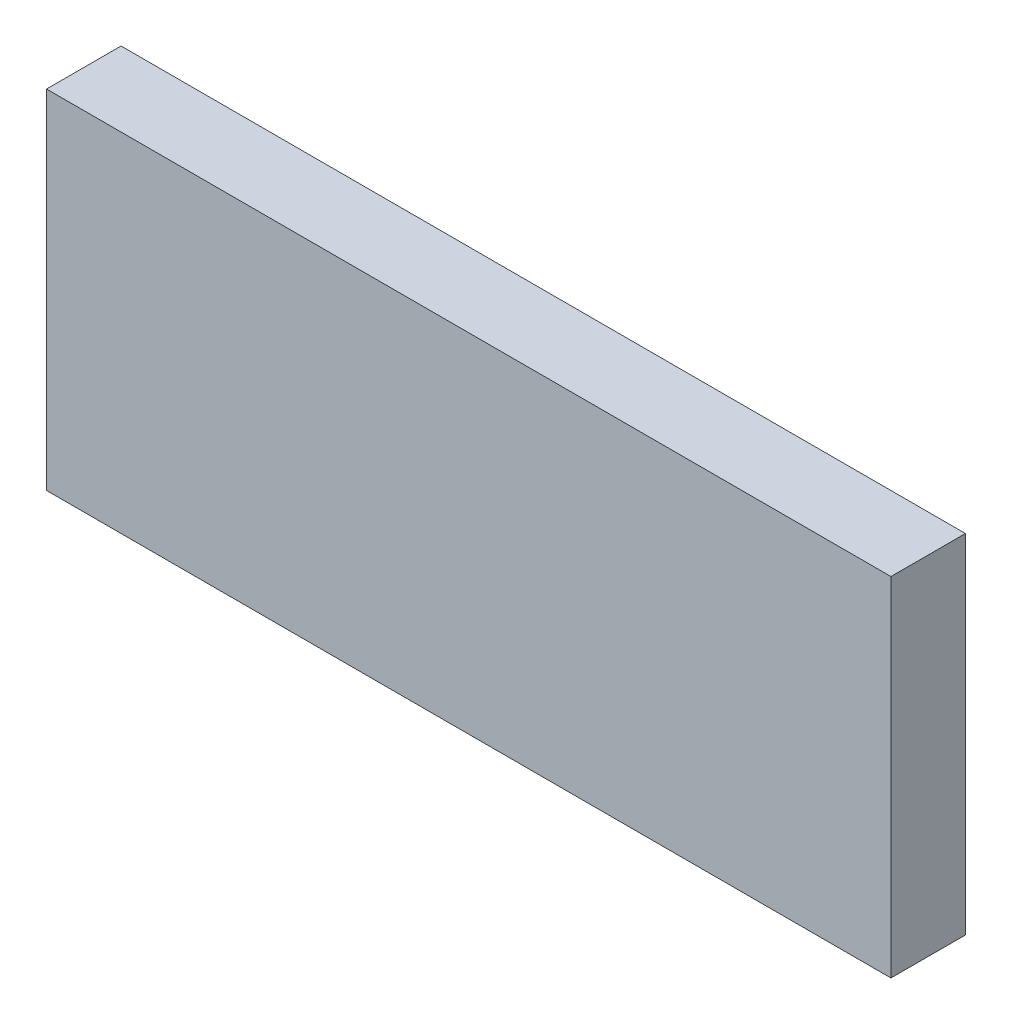
SolidWorks part; units mm, degrees
material "Oak"
ref_plane "Front" through (0, 0, 0) normal (0, 0, 1) x (1, 0, 0)
ref_plane "Top" through (0, 0, 0) normal (0, 1, 0) x (1, 0, 0)
ref_plane "Right" through (0, 0, 0) normal (1, 0, 0) x (0, 0, -1)
sketch "Sketch1" plane through (0, 0, 0) normal (0, 0, 1) x (1, 0, 0)
  line L1 (0, 0) -> (215.9, 0)
  line L2 (0, 0) -> (0, 88.9)
  line L3 (0, 88.9) -> (215.9, 88.9)
  line L4 (215.9, 0) -> (215.9, 88.9)
  dimension "D1" = 215.9
  dimension "D2" = 88.9
extrude "Boss-Extrude1" add sketch "Sketch1" along normal blind 19.05
